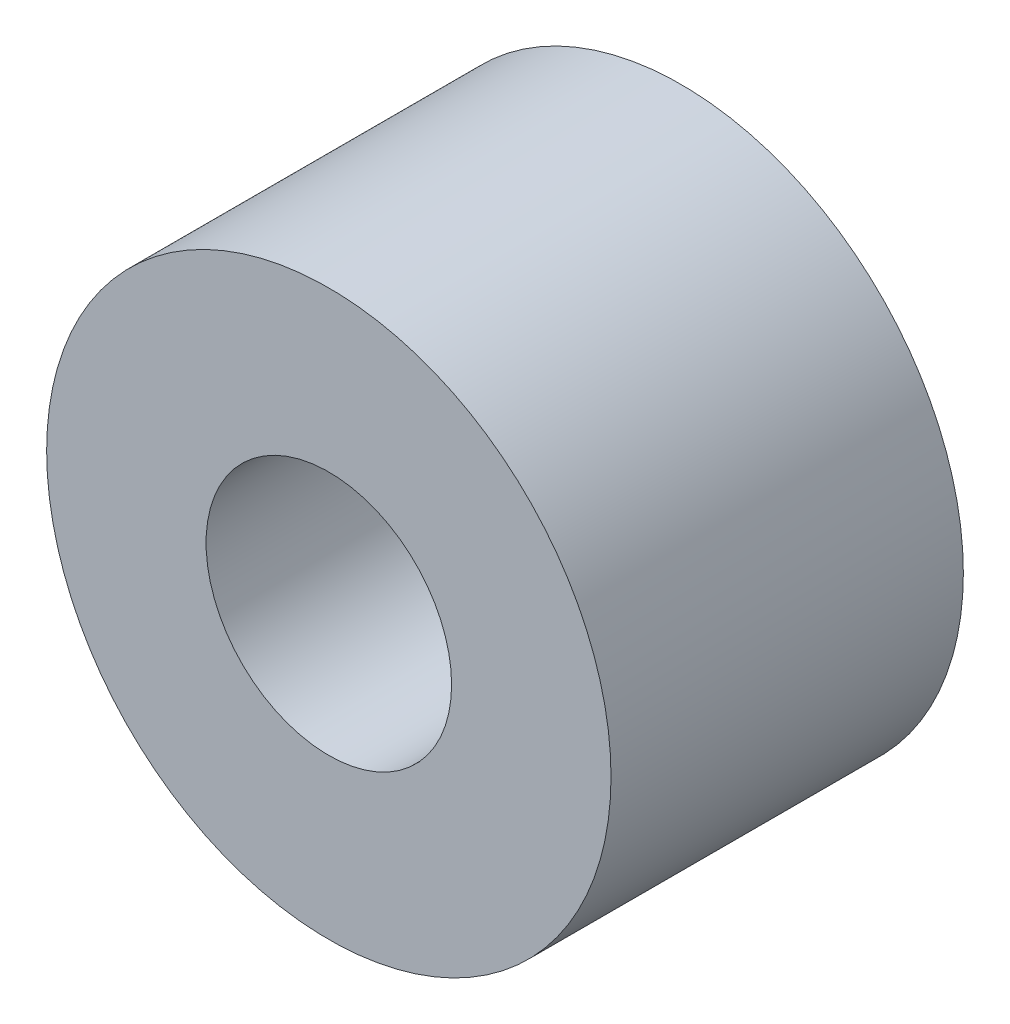
SolidWorks part; units mm, degrees
ref_plane "Front Plane" through (0, 0, 0) normal (0, 0, 1) x (1, 0, 0)
ref_plane "Top Plane" through (0, 0, 0) normal (0, 1, 0) x (1, 0, 0)
ref_plane "Right Plane" through (0, 0, 0) normal (1, 0, 0) x (0, 0, -1)
sketch "Sketch1" plane through (0, 0, 0) normal (0, 0, 1) x (1, 0, 0)
  circle A0 centre (0, 0) radius 4.8895
  circle A1 centre (0, 0) radius 11.2395
  dimension "D1" = 9.779
  dimension "D2" = 6.35
extrude "Boss-Extrude1" add sketch "Sketch1" along normal blind 14.0335
